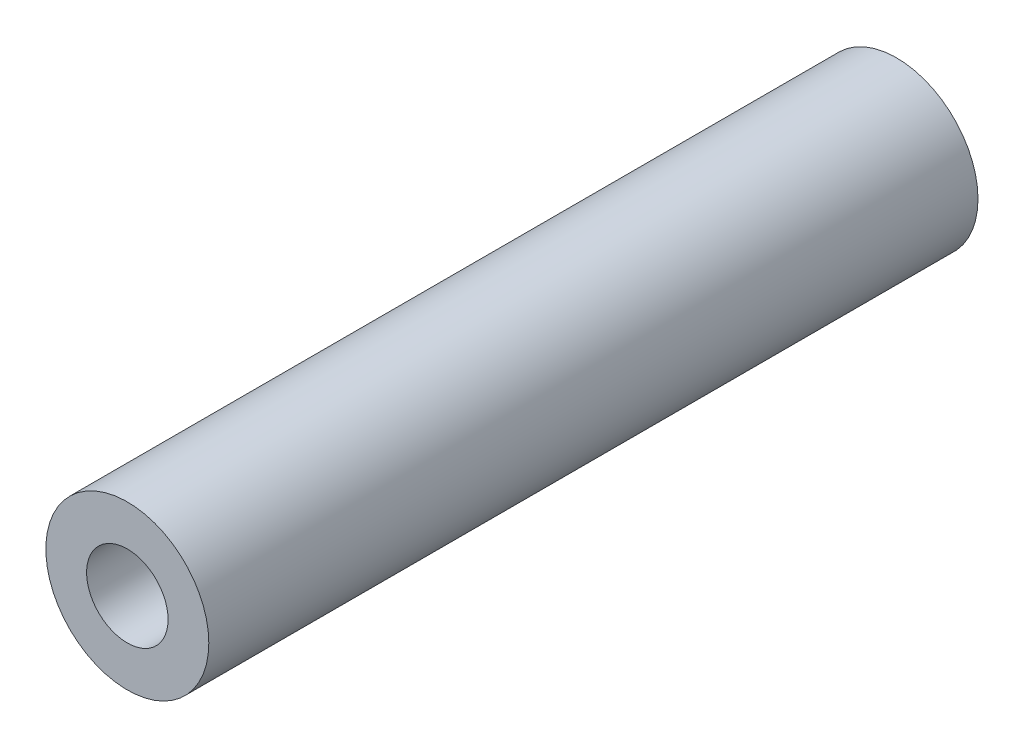
SolidWorks part; units mm, degrees
ref_plane "Front Plane" through (0, 0, 0) normal (0, 0, 1) x (1, 0, 0)
ref_plane "Top Plane" through (0, 0, 0) normal (0, 1, 0) x (1, 0, 0)
ref_plane "Right Plane" through (0, 0, 0) normal (1, 0, 0) x (0, 0, -1)
sketch "Sketch1" plane through (0, 0, 0) normal (0, 0, 1) x (1, 0, 0)
  circle A0 centre (0, 0) radius 0.635
  circle A1 centre (0, 0) radius 0.3175
extrude "Extrude1" add sketch "Sketch1" along normal blind 5.9944
